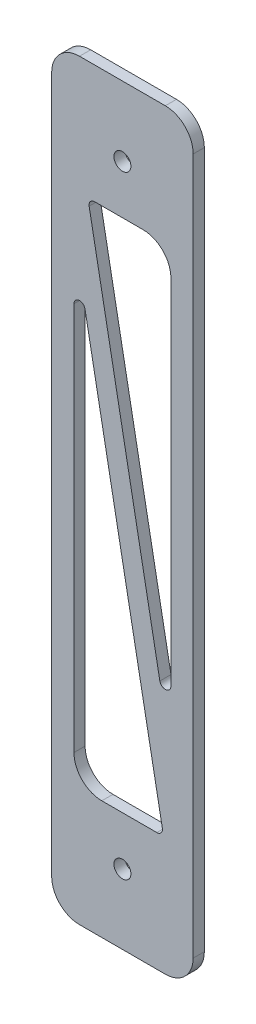
SolidWorks part; units mm, degrees
ref_plane "Front Plane" through (0, 0, 0) normal (0, 0, 1) x (1, 0, 0)
ref_plane "Top Plane" through (0, 0, 0) normal (0, 1, 0) x (1, 0, 0)
ref_plane "Right Plane" through (0, 0, 0) normal (1, 0, 0) x (0, 0, -1)
sketch "Sketch1" plane through (0, 0, 0) normal (0, 0, 1) x (1, 0, 0)
  line L0 (0, 110) -> (0, -110) construction
  line L1 (15.4, -135) -> (-15.4, -135)
  line L2 (25.4, -125) -> (25.4, 125)
  line L3 (15.4, 135) -> (-15.4, 135)
  line L4 (-25.4, -125) -> (-25.4, 125)
  line L5 (25.4, -135) -> (-25.4, 135) construction
  line L6 (25.4, 135) -> (-25.4, -135) construction
  line L7 (-13.4345, 57.4169) -> (14.3225, -90.1105)
  line L8 (12.357, -92.4803) -> (-7.4, -92.4803)
  line L9 (17.4, -44.4592) -> (17.4, 82.4803)
  line L10 (7.4, 92.4803) -> (-9.9886, 92.4803)
  line L11 (-17.4, -82.4803) -> (-17.4, 57.0471)
  line L12 (17.4, -92.4803) -> (-17.4, 92.4803) construction
  line L13 (17.4, 92.4803) -> (-17.4, -92.4803) construction
  line L14 (-11.9541, 90.1105) -> (13.4345, -44.829)
  circle A0 centre (0, 110) radius 3.05
  circle A1 centre (0, -110) radius 3.05
  arc A2 (15.4, -135) -> (25.4, -125) centre (15.4, -125) ccw
  arc A3 (-15.4, -135) -> (-25.4, -125) centre (-15.4, -125) cw
  arc A4 (25.4, 125) -> (15.4, 135) centre (15.4, 125) ccw
  arc A5 (-15.4, 135) -> (-25.4, 125) centre (-15.4, 125) ccw
  arc A7 (-7.4, -92.4803) -> (-17.4, -82.4803) centre (-7.4, -82.4803) cw
  arc A8 (17.4, 82.4803) -> (7.4, 92.4803) centre (7.4, 82.4803) ccw
  arc A9 (17.4, -44.4592) -> (13.4345, -44.829) centre (15.4, -44.4592) cw
  arc A10 (12.357, -92.4803) -> (14.3225, -90.1105) centre (12.357, -90.4803) ccw
  arc A11 (-9.9886, 92.4803) -> (-11.9541, 90.1105) centre (-9.9886, 90.4803) ccw
  arc A12 (-17.4, 57.0471) -> (-13.4345, 57.4169) centre (-15.4, 57.0471) cw
  point P0 (0, 0)
  point P22 (0, 0)
  point P29 (0, 0)
  point P38 (0, 0)
  point P39 (0, 0)
  point P40 (-17.4, 79.8577)
  point P47 (-12.4, 92.4803)
  dimension "D4" = 6.1
  dimension "D5" = 6.1
  dimension "D6" = 10
  dimension "D8" = 7.5
  dimension "D9" = 10
  dimension "D11" = 2
  dimension "D1" = 50.8
  dimension "D2" = 270
  dimension "D3" = 220
  dimension "D7" = 8
  dimension "D10" = 5
extrude "Boss-Extrude1" add sketch "Sketch1" along normal blind 4
